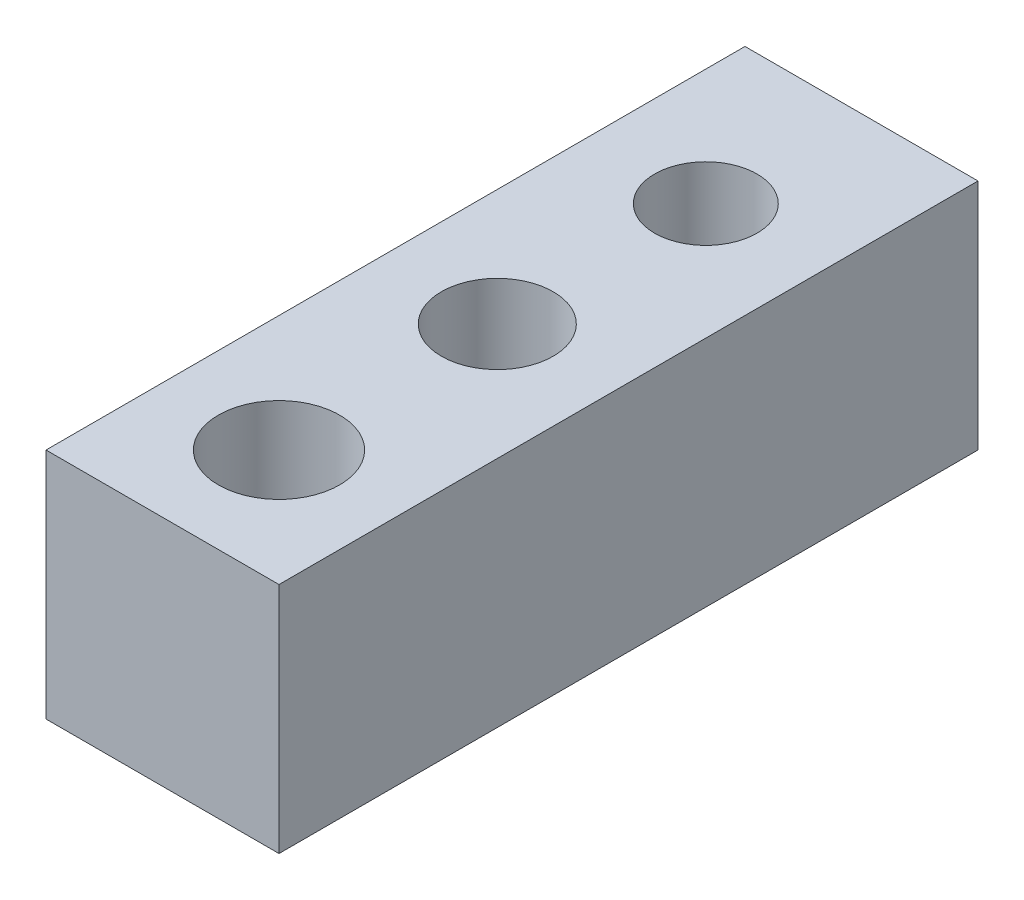
SolidWorks part; units mm, degrees
ref_plane "前视基准面" through (0, 0, 0) normal (0, 0, 1) x (1, 0, 0)
ref_plane "上视基准面" through (0, 0, 0) normal (0, 1, 0) x (1, 0, 0)
ref_plane "右视基准面" through (0, 0, 0) normal (1, 0, 0) x (0, 0, -1)
other "Configuration Table"
sketch "草图1" plane through (0, 0, 0) normal (0, 1, 0) x (1, 0, 0)
  line L1 (-12.8804, 0.788) -> (-7.8804, 0.788)
  line L2 (-12.8804, 0.788) -> (-12.8804, -14.212)
  line L3 (-12.8804, -14.212) -> (-7.8804, -14.212)
  line L4 (-7.8804, 0.788) -> (-7.8804, -14.212)
  dimension "D1" = 5
  dimension "D2" = 15
extrude "凸台-拉伸1" add sketch "草图1" along normal blind 5
sketch "草图2" plane through (0, 5, 0) normal (0, 1, 0) x (1, 0, 0)
  line L0 (-12.8804, -14.212) -> (-7.8804, -14.212) construction
  line L1 (-7.8804, -14.212) -> (-7.8804, 0.788) construction
  circle A0 centre (-10.3804, -11.712) radius 1.3
  circle A1 centre (-10.3804, -7.0276) radius 1.2
  circle A2 centre (-10.3804, -2.553) radius 1.1
  dimension "D1" = 2.5
  dimension "D2" = 2.5
extrude "切除-拉伸1" cut sketch "草图2" against normal blind 5
